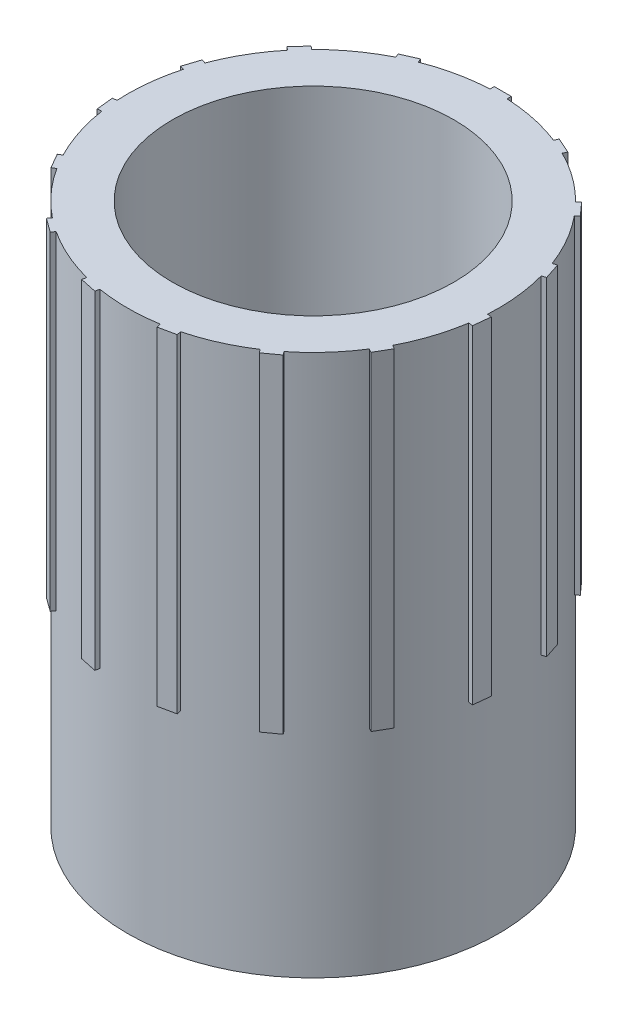
SolidWorks part; units mm, degrees
ref_plane "Front Plane" through (0, 0, 0) normal (0, 0, 1) x (1, 0, 0)
ref_plane "Top Plane" through (0, 0, 0) normal (0, 1, 0) x (1, 0, 0)
ref_plane "Right Plane" through (0, 0, 0) normal (1, 0, 0) x (0, 0, -1)
sketch "Sketch1" plane through (0, 0, 0) normal (0, 1, 0) x (1, 0, 0)
  circle A0 centre (0, 0) radius 4.35
  dimension "D1" = 8.7
extrude "Body" add sketch "Sketch1" along normal blind 12.7
sketch "Sketch2" plane through (0, 12.7, 0) normal (0, 1, 0) x (1, 0, 0)
  line L2 (-0.2, 4.3454) -> (-0.2, 4.4454)
  line L3 (-0.2, 4.4454) -> (0.2, 4.4454)
  line L4 (0.2, 4.3454) -> (0.2, 4.4454)
  circle A0 centre (0, 0) radius 4.35 construction
  arc A1 (0.2, 4.3454) -> (-0.2, 4.3454) centre (0, 0) ccw
  dimension "D1" = 0.1
  dimension "D2" = 0.2
  dimension "D3" = 0.4
extrude "Teeth" add sketch "Sketch2" against normal offset from surface (7.7 mm away) 5 up to face at (0, 0, 4.35)
pattern_circular "CirPattern1" count 15 over 360 about axis through (0, 0, 0) along (0, 1, 0) of "Teeth"
hole_wizard "M6 Clearance Hole1" positions "Sketch3" profile "Sketch4" hole size "M6" standard "ANSI Metric" end condition through all
sketch "Sketch3" plane through (0, 12.7, 0) normal (0, 1, 0) x (1, 0, 0)
  point P0 (0, 0)
sketch "Sketch4" plane through (0, 12.7, 0) normal (1, 0, 0) x (0, 0, 1)
  line L0 (0, 0) -> (0, 12.7)
  line L1 (0, 12.7) -> (3.3, 12.7)
  line L2 (3.3, 12.7) -> (3.3, 0)
  line L5 (3.3, 0) -> (0, 0)
  line L11 (0, -6.35) -> (0, 107.95) construction
  dimension "Thru Hole Dia." = 6.6
  dimension "Thru Hole Depth" = 12.7
